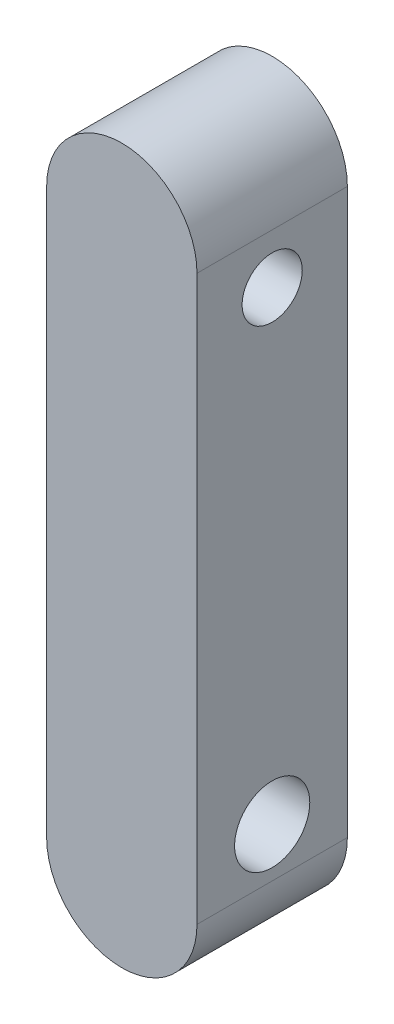
SolidWorks part; units mm, degrees
ref_plane "Front Plane" through (0, 0, 0) normal (0, 0, 1) x (1, 0, 0)
ref_plane "Top Plane" through (0, 0, 0) normal (0, 1, 0) x (1, 0, 0)
ref_plane "Right Plane" through (0, 0, 0) normal (1, 0, 0) x (0, 0, -1)
sketch "Sketch2" plane through (0, 0, 0) normal (0, 0, 1) x (1, 0, 0)
  line L0 (0, 0) -> (0, 75) construction
  line L1 (-10, 0) -> (-10, 75)
  line L2 (10, 0) -> (10, 75)
  arc A0 (-10, 0) -> (10, 0) centre (0, 0) ccw
  arc A1 (10, 75) -> (-10, 75) centre (0, 75) ccw
  circle A2 centre (0, 0) radius 5
  point P2 (0, 37.5)
  dimension "D1" = 20
  dimension "D2" = 75
extrude "Boss-Extrude1" add sketch "Sketch2" along normal blind 20
sketch "Sketch4" plane through (10, 0, 0) normal (1, 0, 0) x (0, 0, -1)
  line L0 (-10, 75) -> (-10, 68.36) construction
  line L1 (-20, 75) -> (0, 75) construction
  circle A0 centre (-10, 68.36) radius 4
  dimension "D1" = 6.64
extrude "Cut-Extrude1" cut sketch "Sketch4" against normal blind 28
sketch "Sketch5" plane through (10, 0, 0) normal (1, 0, 0) x (0, 0, -1)
  line L0 (-10, 0) -> (-10, 6.54) construction
  line L1 (-20, 0) -> (0, 0) construction
  circle A0 centre (-10, 6.54) radius 5
  dimension "D1" = 6.54
extrude "Cut-Extrude2" cut sketch "Sketch5" against normal blind 30
ref_plane "Plane5" through (0, 0, 0) normal (1, 0, 0) x (0, 0, -1)
sketch "Sketch11" plane through (0, 0, 0) normal (1, 0, 0) x (0, 0, -1)
  line L0 (-10, 99.513) -> (-10, 50.487) construction
  line L2 (16.1409, 68.36) -> (-36.1409, 68.36) construction
  point P3 (-10, 75)
  point P7 (-10, 68.36)
sketch "Sketch12" plane through (0, 0, 20) normal (0, 0, 1) x (1, 0, 0)
  circle A0 centre (0, 0) radius 5
extrude "Boss-Extrude2" add sketch "Sketch12" against normal blind 20
sketch "Sketch13" plane through (10, 0, 0) normal (1, 0, 0) x (0, 0, -1)
  circle A0 centre (-10, 6.54) radius 5
extrude "Cut-Extrude3" cut sketch "Sketch13" against normal blind 20
ref_plane "Plane6" through (0, 0, 10) normal (0, 0, 1) x (1, 0, 0)
sketch "Sketch15" plane through (0, 0, 10) normal (0, 0, 1) x (1, 0, 0)
  line L0 (7.9379, 68.36) -> (-6.8405, 68.36) construction
  point P1 (16.8213, 68.36)
  point P2 (19.7, 68.36)
  dimension "D1" = 19.7
ref_plane "Plane7" through (19.7, 0, 0) normal (1, 0, 0) x (0, 0, -1)
sketch "Sketch17" plane through (19.7, 0, 0) normal (1, 0, 0) x (0, 0, -1)
  line L0 (-10, 68.36) -> (83.42, 68.36) construction
  line L1 (200016.1409, 68.36) -> (-200036.1409, 68.36) construction
  dimension "D1" = 93.42
